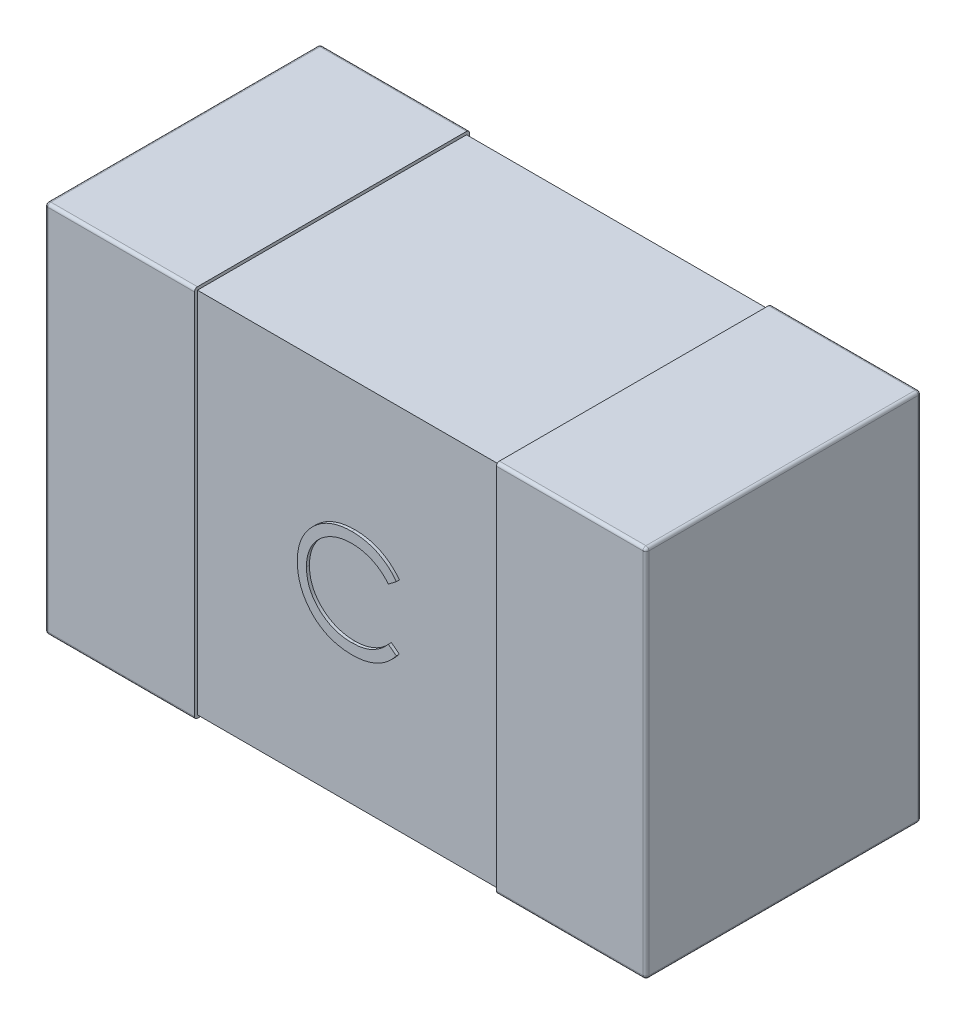
SolidWorks part; units mm, degrees
ref_plane "前视基准面" through (0, 0, 0) normal (0, 0, 1) x (1, 0, 0)
ref_plane "上视基准面" through (0, 0, 0) normal (0, 1, 0) x (1, 0, 0)
ref_plane "右视基准面" through (0, 0, 0) normal (1, 0, 0) x (0, 0, -1)
sketch "草图3" plane through (0, 0, 0) normal (0, 0, 1) x (1, 0, 0)
  line L0 (0, 0.9202) -> (0, -0.6542) construction
  line L1 (-1.005, 0.625) -> (-0.505, 0.625)
  line L2 (-1.005, 0.625) -> (-1.005, -0.625)
  line L3 (-1.005, -0.625) -> (-0.505, -0.625)
  line L4 (-0.505, 0.625) -> (-0.505, -0.625)
  line L5 (-1.005, 0.625) -> (-0.505, -0.625) construction
  line L6 (-1.005, -0.625) -> (-0.505, 0.625) construction
  line L7 (1.005, -0.625) -> (0.505, 0.625) construction
  line L8 (1.005, 0.625) -> (0.505, -0.625) construction
  line L9 (0.505, 0.625) -> (0.505, -0.625)
  line L10 (1.005, -0.625) -> (0.505, -0.625)
  line L11 (1.005, 0.625) -> (1.005, -0.625)
  line L12 (1.005, 0.625) -> (0.505, 0.625)
  point P0 (-0.755, 0)
  point P12 (0.755, 0)
  dimension "D1" = 0.5
  dimension "D2" = 1.25
  dimension "D3" = 1.005
extrude "凸台-拉伸1" add sketch "草图3" along normal blind 0.91 and the other way blind 0.01
sketch "草图5" plane through (0, 0, 0) normal (1, 0, 0) x (0, 0, -1)
  line L0 (0, 0.615) -> (0, -0.615)
  line L1 (0, -0.615) -> (-0.9, -0.615)
  line L2 (-0.9, -0.615) -> (-0.9, 0.615)
  line L3 (-0.9, 0.615) -> (0, 0.615)
  dimension "D1" = 1.23
  dimension "D2" = 0.9
extrude "凸台-拉伸3" add sketch "草图5" along normal mid plane 1.1
fillet "圆角3" radius 0.01 16 edges at (1.005, 0, -0.01) (1.005, -0.625, 0.45) (1.005, 0, 0.91) (1.005, 0.625, 0.45) (-1.005, 0, -0.01) (-1.005, 0.625, 0.45) (-1.005, 0, 0.91) (-1.005, -0.625, 0.45) (0.755, 0.625, -0.01) (0.755, -0.625, -0.01) (0.755, -0.625, 0.91) (0.755, 0.625, 0.91) (-0.755, -0.625, -0.01) (-0.755, -0.625, 0.91) (-0.755, 0.625, -0.01) (-0.755, 0.625, 0.91)
sketch "草图6" plane through (0, 0, 0.9) normal (0, 0, 1) x (1, 0, 0)
  text T0 "C" font "Century Gothic" height 0.34
extrude "凸台-拉伸4" add sketch "草图6" along normal blind 0.01
